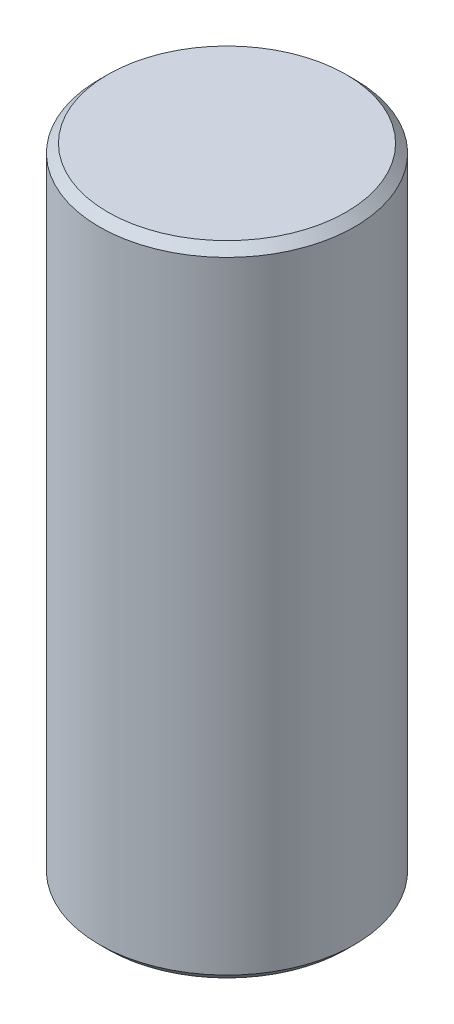
SolidWorks part; units mm, degrees
ref_plane "前视基准面" through (0, 0, 0) normal (0, 0, 1) x (1, 0, 0)
ref_plane "上视基准面" through (0, 0, 0) normal (0, 1, 0) x (1, 0, 0)
ref_plane "右视基准面" through (0, 0, 0) normal (1, 0, 0) x (0, 0, -1)
other "Configuration Table"
sketch "草图1" plane through (0, 0, 0) normal (0, 1, 0) x (1, 0, 0)
  circle A0 centre (0, 0) radius 3
  dimension "D1" = 6
extrude "凸台-拉伸1" add sketch "草图1" along normal blind 15
chamfer "倒角1" distance 0.2 angle 45 2 edges at (0, 0, 3) (0, 15, 3)
